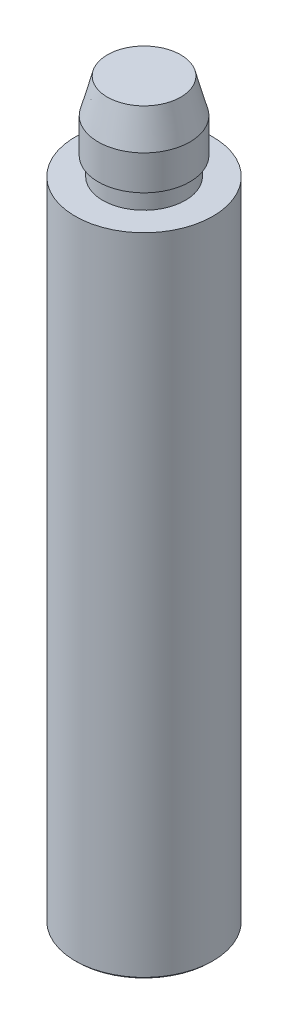
SolidWorks part; units mm, degrees
material "镀铬光轴"
ref_plane "前视" through (0, 0, 0) normal (0, 0, 1) x (1, 0, 0)
ref_plane "上视" through (0, 0, 0) normal (0, 1, 0) x (1, 0, 0)
ref_plane "右视" through (0, 0, 0) normal (1, 0, 0) x (0, 0, -1)
sketch "草图1" plane through (0, 0, 0) normal (0, 0, 1) x (1, 0, 0)
  line L0 (0, -1000) -> (0, 49000) construction
  line L1 (0, 0) -> (7.5, 0)
  line L6 (7.5, 0) -> (7.5, 70.5)
  line L7 (7.5, 70.5) -> (4.5, 70.5)
  line L8 (4.5, 70.5) -> (4.5, 72.5)
  line L9 (4.5, 72.5) -> (5, 72.5)
  line L10 (5, 72.5) -> (5, 76.2679)
  line L11 (5, 76.2679) -> (4, 80)
  line L12 (4, 80) -> (0, 80)
  line L13 (0, 80) -> (0, 0)
  dimension "D4" = 15
  dimension "D5" = 15
  dimension "D6" = 2
  dimension "D7" = 9
  dimension "D8" = 10
  dimension "D9" = 9.5
  dimension "D11" = 8
  dimension "D12" = 80
revolve "旋转1" add sketch "草图1" angle 360 about L0
hole_wizard "M6 螺纹孔1" positions "草图3" profile "草图2" tap size "M6" standard "Gb"
sketch "草图3" plane through (0, 0, 0) normal (0, -1, 0) x (-1, 0, 0)
  point P0 (0, 0)
sketch "草图2" plane through (0, 0, 0) normal (1, 0, 0) x (0, 0, -1)
  line L0 (0, 0) -> (0, 16.5022)
  line L1 (0, 16.5022) -> (2.5, 15)
  line L2 (2.5, 15) -> (2.5, 0)
  line L5 (2.5, 0) -> (0, 0)
  line L10 (0, 16.5022) -> (-2.5, 15) construction
  line L11 (0, -6.35) -> (0, 107.95) construction
  dimension "螺纹孔钻头直径" = 5
  dimension "螺纹孔钻头深度" = 15
  dimension "导头角度" = 118
cosmetic thread "孔螺蚊线1" parameters "D1"=12, "D2"=6
chamfer "倒角1" distance 0.2 angle 45 1 edges at (7.5, 0, 0)
